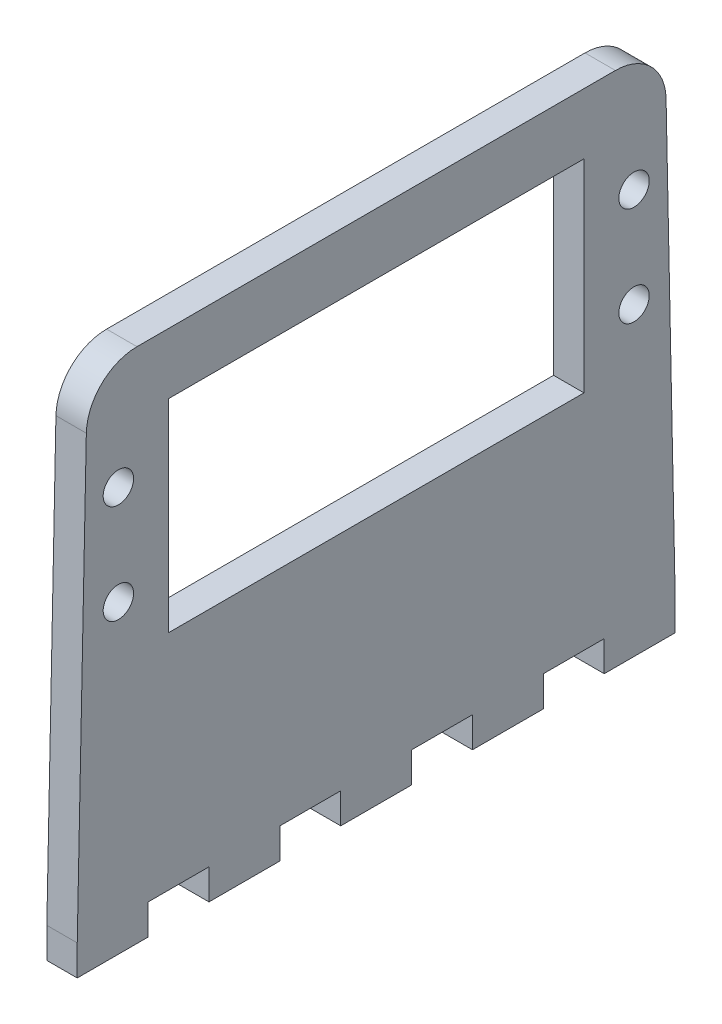
SolidWorks part; units mm, degrees
material "Perspex (TM) GS Acrylic Cast Sheet"
ref_plane "Front Plane" through (0, 0, 0) normal (0, 0, 1) x (1, 0, 0)
ref_plane "Top Plane" through (0, 0, 0) normal (0, 1, 0) x (1, 0, 0)
ref_plane "Right Plane" through (0, 0, 0) normal (1, 0, 0) x (0, 0, -1)
sketch "Sketch1" plane through (0, 0, 0) normal (1, 0, 0) x (0, 0, -1)
  line L0 (-33, 0) -> (-32, 48)
  line L1 (-32, 48) -> (25, 48)
  line L2 (25, 48) -> (26, 0)
  line L3 (26, 0) -> (26, -3)
  line L4 (26, -3) -> (19, -3)
  line L5 (19, -3) -> (19, 0)
  line L6 (19, 0) -> (13, 0)
  line L7 (13, 0) -> (13, -3)
  line L8 (13, -3) -> (6, -3)
  line L9 (6, -3) -> (6, 0)
  line L10 (6, 0) -> (0, 0)
  line L11 (0, 0) -> (0, -3)
  line L12 (0, -3) -> (-7, -3)
  line L13 (-7, -3) -> (-7, 0)
  line L14 (-7, 0) -> (-13, 0)
  line L15 (-13, 0) -> (-13, -3)
  line L16 (-13, -3) -> (-20, -3)
  line L17 (-20, -3) -> (-20, 0)
  line L18 (-20, 0) -> (-26, 0)
  line L19 (-26, 0) -> (-26, -3)
  line L20 (-26, -3) -> (-33, -3)
  line L21 (-33, -3) -> (-33, 0)
  line L22 (-3.5, 32) -> (-3.5, 37.1865) construction
  line L23 (-24, 42) -> (17, 42)
  line L24 (-24, 42) -> (-24, 22)
  line L25 (-24, 22) -> (17, 22)
  line L26 (17, 42) -> (17, 22)
  line L27 (-24, 42) -> (17, 22) construction
  line L28 (-24, 22) -> (17, 42) construction
  line L29 (-3.5, 32) -> (1.6461, 32) construction
  circle A0 centre (21.94, 36.9) radius 1.5
  circle A1 centre (21.94, 27.1) radius 1.5
  circle A2 centre (-28.94, 36.9) radius 1.5
  circle A3 centre (-28.94, 27.1) radius 1.5
  point P23 (-3.5, 32)
  point P38 (-3.5, -3)
  dimension "D7" = 22
  dimension "D8" = 3
  dimension "D1" = 7
  dimension "D2" = 3
  dimension "D3" = 6
  dimension "D4" = 20
  dimension "D5" = 41
  dimension "D6" = 6
  dimension "D9" = 5.1
  dimension "D10" = 4.94
  dimension "D12" = 57
extrude "Boss-Extrude1" add sketch "Sketch1" along normal blind 3
fillet "Fillet1" radius 5 2 edges at (1.5, 48, 32) (1.5, 48, -25)
